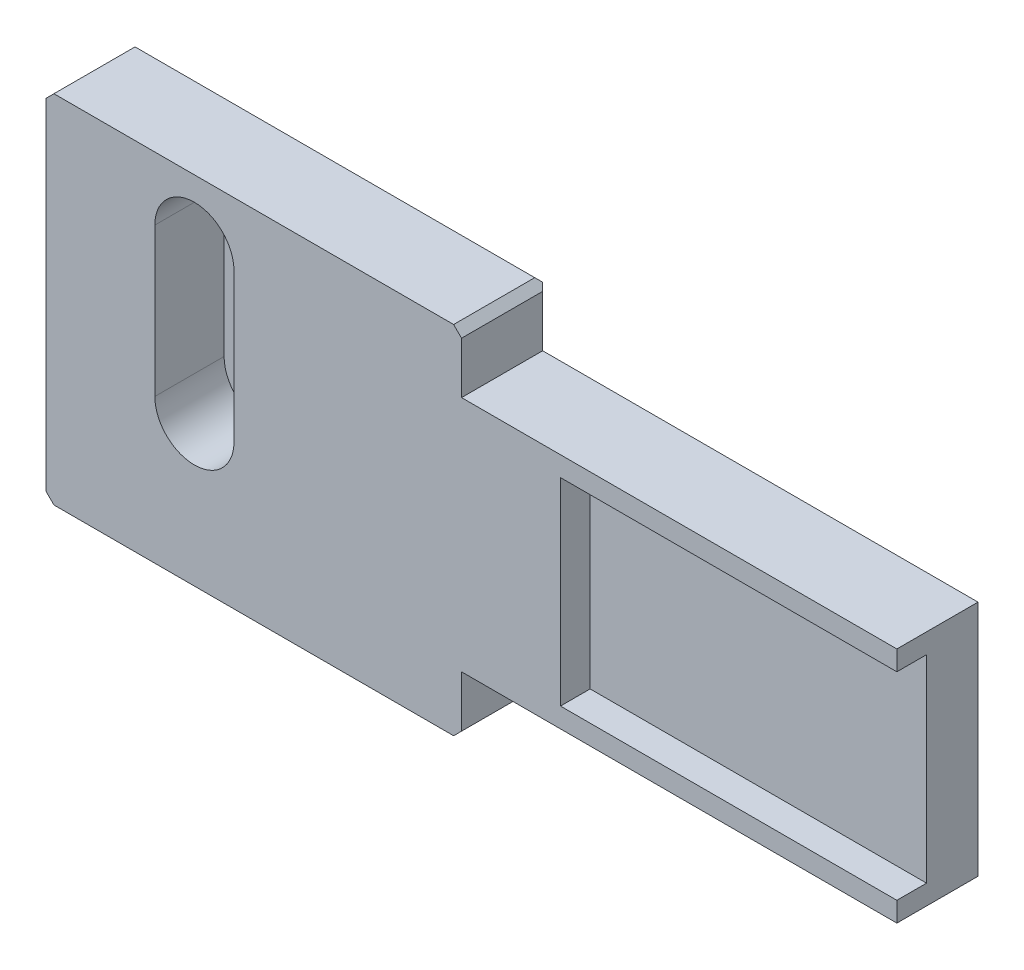
SolidWorks part; units mm, degrees
ref_plane "Front Plane" through (0, 0, 0) normal (0, 0, 1) x (1, 0, 0)
ref_plane "Top Plane" through (0, 0, 0) normal (0, 1, 0) x (1, 0, 0)
ref_plane "Right Plane" through (0, 0, 0) normal (1, 0, 0) x (0, 0, -1)
ref_plane "Plane1" through (0, 0, 0) normal (0, 0, -1) x (-1, 0, 0)
sketch "Sketch1" plane through (0, 0, 0) normal (0, 0, -1) x (-1, 0, 0)
  line L0 (-43, 18) -> (-43, 0)
  line L1 (-43, 0) -> (0, 0)
  line L2 (0, 0) -> (0, 18)
  line L3 (0, 18) -> (-43, 18)
extrude "Boss-Extrude1" add sketch "Sketch1" against normal blind 4.5
sketch "Sketch2" plane through (0, 0, 4.5) normal (0, 0, 1) x (1, 0, 0)
  line L0 (43, 0) -> (43, 3)
  line L1 (43, 3) -> (21, 3)
  line L2 (21, 3) -> (21, 0)
  line L3 (21, 0) -> (43, 0)
extrude "Cut-Extrude1" cut sketch "Sketch2" against normal through all
sketch "Sketch3" plane through (0, 0, 4.5) normal (0, 0, 1) x (1, 0, 0)
  line L0 (21, 15) -> (43, 15)
  line L1 (43, 15) -> (43, 18)
  line L2 (43, 18) -> (21, 18)
  line L3 (21, 18) -> (21, 15)
extrude "Cut-Extrude2" cut sketch "Sketch3" against normal through all
sketch "Sketch4" plane through (0, 0, 4.5) normal (0, 0, 1) x (1, 0, 0)
  line L0 (8.6675, 16.4239) -> (8.5851, 16.48) construction
  line L1 (8.5851, 16.48) -> (8.5, 16.532) construction
  line L2 (8.5, 16.532) -> (8.4124, 16.5797) construction
  line L3 (8.4124, 16.5797) -> (8.3226, 16.623) construction
  line L4 (8.3226, 16.623) -> (8.2307, 16.6617) construction
  line L5 (8.2307, 16.6617) -> (8.137, 16.6959) construction
  line L6 (8.137, 16.6959) -> (8.0417, 16.7253) construction
  line L7 (8.0417, 16.7253) -> (7.945, 16.7499) construction
  line L8 (7.945, 16.7499) -> (7.8473, 16.7696) construction
  line L9 (7.8473, 16.7696) -> (7.7487, 16.7845) construction
  line L10 (7.7487, 16.7845) -> (7.6495, 16.7944) construction
  line L11 (7.6495, 16.7944) -> (7.5499, 16.7994) construction
  line L12 (7.5499, 16.7994) -> (7.4501, 16.7994) construction
  line L13 (7.4501, 16.7994) -> (7.3505, 16.7944) construction
  line L14 (7.3505, 16.7944) -> (7.2513, 16.7845) construction
  line L15 (7.2513, 16.7845) -> (7.1527, 16.7696) construction
  line L16 (7.1527, 16.7696) -> (7.055, 16.7499) construction
  line L17 (7.055, 16.7499) -> (6.9583, 16.7253) construction
  line L18 (6.9583, 16.7253) -> (6.863, 16.6959) construction
  line L19 (6.863, 16.6959) -> (6.7693, 16.6617) construction
  line L20 (6.7693, 16.6617) -> (6.6774, 16.623) construction
  line L21 (6.6774, 16.623) -> (6.5876, 16.5797) construction
  line L22 (6.5876, 16.5797) -> (6.5, 16.532) construction
  line L23 (6.5, 16.532) -> (6.4149, 16.48) construction
  line L24 (6.4149, 16.48) -> (6.3325, 16.4239) construction
  line L25 (6.3325, 16.4239) -> (6.253, 16.3637) construction
  line L26 (6.253, 16.3637) -> (6.1766, 16.2996) construction
  line L27 (6.1766, 16.2996) -> (6.1035, 16.2317) construction
  line L28 (6.1035, 16.2317) -> (6.0339, 16.1603) construction
  line L29 (6.0339, 16.1603) -> (5.9679, 16.0856) construction
  line L30 (5.9679, 16.0856) -> (5.9057, 16.0076) construction
  line L31 (5.9057, 16.0076) -> (5.8475, 15.9266) construction
  line L32 (5.8475, 15.9266) -> (5.7934, 15.8429) construction
  line L33 (5.7934, 15.8429) -> (5.7436, 15.7565) construction
  line L34 (5.7436, 15.7565) -> (5.6981, 15.6678) construction
  line L35 (5.6981, 15.6678) -> (5.6571, 15.5769) construction
  line L36 (5.6571, 15.5769) -> (5.6206, 15.484) construction
  line L37 (5.6206, 15.484) -> (5.5889, 15.3895) construction
  line L38 (5.5889, 15.3895) -> (5.5618, 15.2935) construction
  line L39 (5.5618, 15.2935) -> (5.5396, 15.1963) construction
  line L40 (5.5396, 15.1963) -> (5.5223, 15.0981) construction
  line L41 (5.5223, 15.0981) -> (5.5099, 14.9991) construction
  line L42 (5.5099, 14.9991) -> (5.5025, 14.8997) construction
  line L43 (5.5025, 14.8997) -> (5.5, 14.8) construction
  line L44 (5.5, 14.8) -> (5.5, 7.3) construction
  line L45 (5.5, 7.3) -> (5.5025, 7.2003) construction
  line L46 (5.5025, 7.2003) -> (5.5099, 7.1009) construction
  line L47 (5.5099, 7.1009) -> (5.5223, 7.0019) construction
  line L48 (5.5223, 7.0019) -> (5.5396, 6.9037) construction
  line L49 (5.5396, 6.9037) -> (5.5618, 6.8065) construction
  line L50 (5.5618, 6.8065) -> (5.5889, 6.7105) construction
  line L51 (5.5889, 6.7105) -> (5.6206, 6.616) construction
  line L52 (5.6206, 6.616) -> (5.6571, 6.5231) construction
  line L53 (5.6571, 6.5231) -> (5.6981, 6.4322) construction
  line L54 (5.6981, 6.4322) -> (5.7436, 6.3435) construction
  line L55 (5.7436, 6.3435) -> (5.7934, 6.2571) construction
  line L56 (5.7934, 6.2571) -> (5.8475, 6.1734) construction
  line L57 (5.8475, 6.1734) -> (5.9057, 6.0924) construction
  line L58 (5.9057, 6.0924) -> (5.9679, 6.0144) construction
  line L59 (5.9679, 6.0144) -> (6.0339, 5.9396) construction
  line L60 (6.0339, 5.9396) -> (6.1035, 5.8683) construction
  line L61 (6.1035, 5.8683) -> (6.1766, 5.8004) construction
  line L62 (6.1766, 5.8004) -> (6.253, 5.7363) construction
  line L63 (6.253, 5.7363) -> (6.3325, 5.6761) construction
  line L64 (6.3325, 5.6761) -> (6.4149, 5.6199) construction
  line L65 (6.4149, 5.6199) -> (6.5, 5.568) construction
  line L66 (6.5, 5.568) -> (6.5876, 5.5203) construction
  line L67 (6.5876, 5.5203) -> (6.6774, 5.477) construction
  line L68 (6.6774, 5.477) -> (6.7693, 5.4382) construction
  line L69 (6.7693, 5.4382) -> (6.863, 5.4042) construction
  line L70 (6.863, 5.4042) -> (6.9583, 5.3747) construction
  line L71 (6.9583, 5.3747) -> (7.055, 5.3501) construction
  line L72 (7.055, 5.3501) -> (7.1527, 5.3304) construction
  line L73 (7.1527, 5.3304) -> (7.2513, 5.3155) construction
  line L74 (7.2513, 5.3155) -> (7.3505, 5.3056) construction
  line L75 (7.3505, 5.3056) -> (7.4501, 5.3006) construction
  line L76 (7.4501, 5.3006) -> (7.5499, 5.3006) construction
  line L77 (7.5499, 5.3006) -> (7.6495, 5.3056) construction
  line L78 (7.6495, 5.3056) -> (7.7487, 5.3155) construction
  line L79 (7.7487, 5.3155) -> (7.8473, 5.3304) construction
  line L80 (7.8473, 5.3304) -> (7.945, 5.3501) construction
  line L81 (7.945, 5.3501) -> (8.0417, 5.3747) construction
  line L82 (8.0417, 5.3747) -> (8.137, 5.4042) construction
  line L83 (8.137, 5.4042) -> (8.2307, 5.4382) construction
  line L84 (8.2307, 5.4382) -> (8.3226, 5.477) construction
  line L85 (8.3226, 5.477) -> (8.4124, 5.5203) construction
  line L86 (8.4124, 5.5203) -> (8.5, 5.568) construction
  line L87 (8.5, 5.568) -> (8.5851, 5.6199) construction
  line L88 (8.5851, 5.6199) -> (8.6675, 5.6761) construction
  line L89 (8.6675, 5.6761) -> (8.747, 5.7363) construction
  line L90 (8.747, 5.7363) -> (8.8234, 5.8004) construction
  line L91 (8.8234, 5.8004) -> (8.8965, 5.8683) construction
  line L92 (8.8965, 5.8683) -> (8.9661, 5.9396) construction
  line L93 (8.9661, 5.9396) -> (9.0321, 6.0144) construction
  line L94 (9.0321, 6.0144) -> (9.0943, 6.0924) construction
  line L95 (9.0943, 6.0924) -> (9.1525, 6.1734) construction
  line L96 (9.1525, 6.1734) -> (9.2066, 6.2571) construction
  line L97 (9.2066, 6.2571) -> (9.2564, 6.3435) construction
  line L98 (9.2564, 6.3435) -> (9.3019, 6.4322) construction
  line L99 (9.3019, 6.4322) -> (9.3429, 6.5231) construction
  line L100 (9.3429, 6.5231) -> (9.3794, 6.616) construction
  line L101 (9.3794, 6.616) -> (9.4111, 6.7105) construction
  line L102 (9.4111, 6.7105) -> (9.4382, 6.8065) construction
  line L103 (9.4382, 6.8065) -> (9.4604, 6.9037) construction
  line L104 (9.4604, 6.9037) -> (9.4777, 7.0019) construction
  line L105 (9.4777, 7.0019) -> (9.4901, 7.1009) construction
  line L106 (9.4901, 7.1009) -> (9.4975, 7.2003) construction
  line L107 (9.4975, 7.2003) -> (9.5, 7.3) construction
  line L108 (9.5, 7.3) -> (9.5, 14.8) construction
  line L109 (9.5, 14.8) -> (9.4975, 14.8997) construction
  line L110 (9.4975, 14.8997) -> (9.4901, 14.9991) construction
  line L111 (9.4901, 14.9991) -> (9.4777, 15.0981) construction
  line L112 (9.4777, 15.0981) -> (9.4604, 15.1963) construction
  line L113 (9.4604, 15.1963) -> (9.4382, 15.2935) construction
  line L114 (9.4382, 15.2935) -> (9.4111, 15.3895) construction
  line L115 (9.4111, 15.3895) -> (9.3794, 15.484) construction
  line L116 (9.3794, 15.484) -> (9.3429, 15.5769) construction
  line L117 (9.3429, 15.5769) -> (9.3019, 15.6678) construction
  line L118 (9.3019, 15.6678) -> (9.2564, 15.7565) construction
  line L119 (9.2564, 15.7565) -> (9.2066, 15.8429) construction
  line L120 (9.2066, 15.8429) -> (9.1525, 15.9266) construction
  line L121 (9.1525, 15.9266) -> (9.0943, 16.0076) construction
  line L122 (9.0943, 16.0076) -> (9.0321, 16.0856) construction
  line L123 (9.0321, 16.0856) -> (8.9661, 16.1603) construction
  line L124 (8.9661, 16.1603) -> (8.8965, 16.2317) construction
  line L125 (8.8965, 16.2317) -> (8.8234, 16.2996) construction
  line L126 (8.8234, 16.2996) -> (8.747, 16.3637) construction
  line L127 (8.747, 16.3637) -> (8.6675, 16.4239) construction
  line L128 (5.5, 14.8) -> (9.5, 14.8) construction
  line L129 (5.5, 7.3) -> (9.5, 7.3) construction
  line L130 (7.5, 14.8) -> (7.5, 7.3) construction
  line L131 (9.5, 14.8) -> (9.5, 7.3)
  line L132 (5.5, 14.8) -> (5.5, 7.3)
  arc A0 (9.5, 14.8) -> (5.5, 14.8) centre (7.5, 14.8) ccw
  arc A1 (5.5, 7.3) -> (9.5, 7.3) centre (7.5, 7.3) ccw
  point P130 (7.5, 11.05)
extrude "Cut-Extrude3" cut sketch "Sketch4" against normal blind 3.5
sketch "Sketch5" plane through (0, 0, 0) normal (0, 0, -1) x (-1, 0, 0)
  line L0 (-6.3367, 15.0946) -> (-6.365, 15.1896) construction
  line L1 (-6.365, 15.1896) -> (-6.4011, 15.282) construction
  line L2 (-6.4011, 15.282) -> (-6.4446, 15.3711) construction
  line L3 (-6.4446, 15.3711) -> (-6.4954, 15.4563) construction
  line L4 (-6.4954, 15.4563) -> (-6.553, 15.5371) construction
  line L5 (-6.553, 15.5371) -> (-6.6171, 15.6127) construction
  line L6 (-6.6171, 15.6127) -> (-6.6873, 15.6829) construction
  line L7 (-6.6873, 15.6829) -> (-6.7629, 15.747) construction
  line L8 (-6.7629, 15.747) -> (-6.8437, 15.8046) construction
  line L9 (-6.8437, 15.8046) -> (-6.9289, 15.8554) construction
  line L10 (-6.9289, 15.8554) -> (-7.018, 15.8989) construction
  line L11 (-7.018, 15.8989) -> (-7.1104, 15.935) construction
  line L12 (-7.1104, 15.935) -> (-7.2054, 15.9633) construction
  line L13 (-7.2054, 15.9633) -> (-7.3025, 15.9836) construction
  line L14 (-7.3025, 15.9836) -> (-7.4009, 15.9959) construction
  line L15 (-7.4009, 15.9959) -> (-7.5, 16) construction
  line L16 (-7.5, 16) -> (-7.5991, 15.9959) construction
  line L17 (-7.5991, 15.9959) -> (-7.6975, 15.9836) construction
  line L18 (-7.6975, 15.9836) -> (-7.7946, 15.9633) construction
  line L19 (-7.7946, 15.9633) -> (-7.8896, 15.935) construction
  line L20 (-7.8896, 15.935) -> (-7.982, 15.8989) construction
  line L21 (-7.982, 15.8989) -> (-8.0711, 15.8554) construction
  line L22 (-8.0711, 15.8554) -> (-8.1563, 15.8046) construction
  line L23 (-8.1563, 15.8046) -> (-8.2371, 15.747) construction
  line L24 (-8.2371, 15.747) -> (-8.3127, 15.6829) construction
  line L25 (-8.3127, 15.6829) -> (-8.3829, 15.6127) construction
  line L26 (-8.3829, 15.6127) -> (-8.447, 15.5371) construction
  line L27 (-8.447, 15.5371) -> (-8.5046, 15.4563) construction
  line L28 (-8.5046, 15.4563) -> (-8.5554, 15.3711) construction
  line L29 (-8.5554, 15.3711) -> (-8.5989, 15.282) construction
  line L30 (-8.5989, 15.282) -> (-8.635, 15.1896) construction
  line L31 (-8.635, 15.1896) -> (-8.6633, 15.0946) construction
  line L32 (-8.6633, 15.0946) -> (-8.6836, 14.9975) construction
  line L33 (-8.6836, 14.9975) -> (-8.6959, 14.8991) construction
  line L34 (-8.6959, 14.8991) -> (-8.7, 14.8) construction
  line L35 (-8.7, 14.8) -> (-8.5, 7.3) construction
  line L36 (-8.5, 7.3) -> (-8.495, 7.2004) construction
  line L37 (-8.495, 7.2004) -> (-8.4802, 7.1019) construction
  line L38 (-8.4802, 7.1019) -> (-8.4556, 7.0052) construction
  line L39 (-8.4556, 7.0052) -> (-8.4215, 6.9116) construction
  line L40 (-8.4215, 6.9116) -> (-8.3782, 6.8217) construction
  line L41 (-8.3782, 6.8217) -> (-8.3262, 6.7367) construction
  line L42 (-8.3262, 6.7367) -> (-8.266, 6.6572) construction
  line L43 (-8.266, 6.6572) -> (-8.1982, 6.5841) construction
  line L44 (-8.1982, 6.5841) -> (-8.1235, 6.5182) construction
  line L45 (-8.1235, 6.5182) -> (-8.0425, 6.46) construction
  line L46 (-8.0425, 6.46) -> (-7.9562, 6.4101) construction
  line L47 (-7.9562, 6.4101) -> (-7.8653, 6.3691) construction
  line L48 (-7.8653, 6.3691) -> (-7.7708, 6.3374) construction
  line L49 (-7.7708, 6.3374) -> (-7.6736, 6.3152) construction
  line L50 (-7.6736, 6.3152) -> (-7.5747, 6.3028) construction
  line L51 (-7.5747, 6.3028) -> (-7.4751, 6.3003) construction
  line L52 (-7.4751, 6.3003) -> (-7.3757, 6.3078) construction
  line L53 (-7.3757, 6.3078) -> (-7.2775, 6.3251) construction
  line L54 (-7.2775, 6.3251) -> (-7.1815, 6.3521) construction
  line L55 (-7.1815, 6.3521) -> (-7.0887, 6.3885) construction
  line L56 (-7.0887, 6.3885) -> (-7, 6.434) construction
  line L57 (-7, 6.434) -> (-6.9163, 6.4881) construction
  line L58 (-6.9163, 6.4881) -> (-6.8383, 6.5502) construction
  line L59 (-6.8383, 6.5502) -> (-6.7669, 6.6198) construction
  line L60 (-6.7669, 6.6198) -> (-6.7029, 6.6962) construction
  line L61 (-6.7029, 6.6962) -> (-6.6467, 6.7786) construction
  line L62 (-6.6467, 6.7786) -> (-6.599, 6.8661) construction
  line L63 (-6.599, 6.8661) -> (-6.5603, 6.958) construction
  line L64 (-6.5603, 6.958) -> (-6.5309, 7.0532) construction
  line L65 (-6.5309, 7.0532) -> (-6.5112, 7.151) construction
  line L66 (-6.5112, 7.151) -> (-6.5012, 7.2502) construction
  line L67 (-6.5012, 7.2502) -> (-6.3, 14.8) construction
  line L68 (-6.3, 14.8) -> (-6.3041, 14.8991) construction
  line L69 (-6.3041, 14.8991) -> (-6.3164, 14.9975) construction
  line L70 (-6.3164, 14.9975) -> (-6.3367, 15.0946) construction
  line L71 (-8.7, 14.8) -> (-6.3, 14.8) construction
  line L72 (-8.5, 7.3) -> (-6.5012, 7.2502) construction
  line L73 (-7.5, 14.8) -> (-7.5006, 7.2751) construction
  line L74 (-7.5, 14.8) -> (-7.5006, 7.2751) construction
  line L75 (-6.3, 14.7999) -> (-6.3006, 7.275)
  line L76 (-8.7, 14.8001) -> (-8.7006, 7.2752)
  arc A0 (-6.3, 14.7999) -> (-8.7, 14.8001) centre (-7.5, 14.8) ccw
  arc A1 (-8.7006, 7.2752) -> (-6.3006, 7.275) centre (-7.5006, 7.2751) ccw
  point P73 (-7.5003, 11.0375)
extrude "Cut-Extrude4" cut sketch "Sketch5" against normal through all
sketch "Sketch6" plane through (43, 0, 0) normal (1, 0, 0) x (0, 0, -1)
  line L0 (-4.5, 4) -> (-3, 4)
  line L1 (-3, 4) -> (-3, 14)
  line L2 (-3, 14) -> (-4.5, 14)
  line L3 (-4.5, 14) -> (-4.5, 4)
extrude "Cut-Extrude5" cut sketch "Sketch6" against normal blind 17
chamfer "Chamfer1" distance 0.4 12 edges at (10.5, 18, 0) (0, 9, 0) (10.5, 0, 0) (21, 1.5, 0) (32, 3, 0) (43, 9, 0) (32, 15, 0) (21, 16.5, 0) (8.7003, 11.0376, 0) (7.5007, 6.0751, 0) (6.3003, 11.0374, 0) (7.4999, 16, 0)
chamfer "Chamfer2" distance 0.4 4 edges at (21, 0, 2.45) (0, 0, 2.45) (0, 18, 2.45) (21, 18, 2.45)
